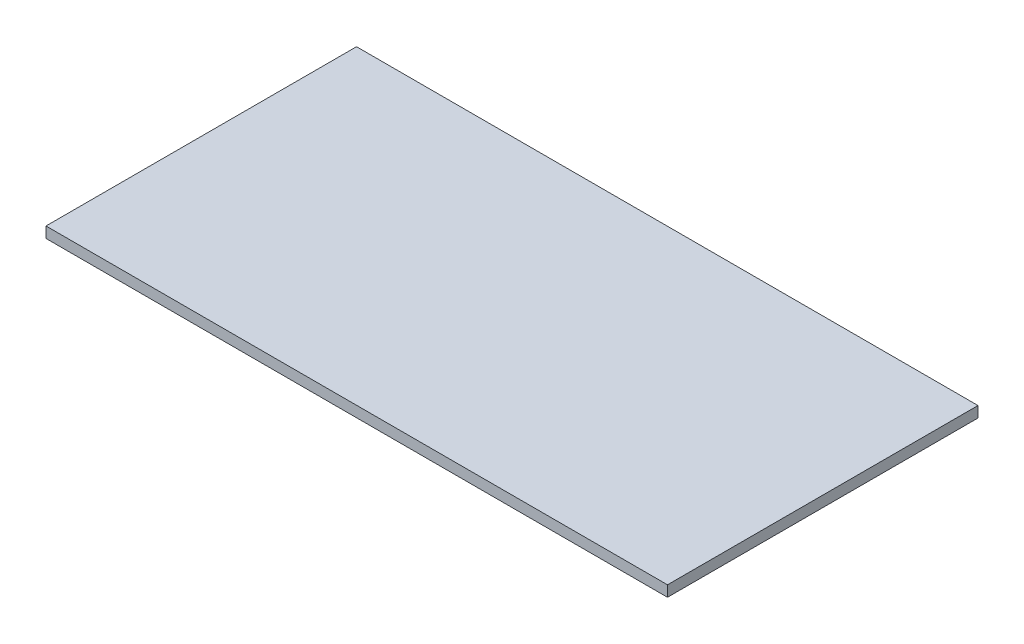
SolidWorks part; units mm, degrees
material "玻璃"
ref_plane "前视基准面" through (0, 0, 0) normal (0, 0, 1) x (1, 0, 0)
ref_plane "上视基准面" through (0, 0, 0) normal (0, 1, 0) x (1, 0, 0)
ref_plane "右视基准面" through (0, 0, 0) normal (1, 0, 0) x (0, 0, -1)
other "Configuration Table"
sketch "草图1" plane through (0, 0, 0) normal (0, 1, 0) x (1, 0, 0)
  line L1 (-65.95, 32.95) -> (65.95, 32.95)
  line L2 (-65.95, 32.95) -> (-65.95, -32.95)
  line L3 (-65.95, -32.95) -> (65.95, -32.95)
  line L4 (65.95, 32.95) -> (65.95, -32.95)
  line L5 (-65.95, 32.95) -> (65.95, -32.95) construction
  line L6 (-65.95, -32.95) -> (65.95, 32.95) construction
  point P0 (0, 0)
  dimension "D1" = 65.9
  dimension "D2" = 131.9
extrude "凸台-拉伸1" add sketch "草图1" along normal blind 2.3
